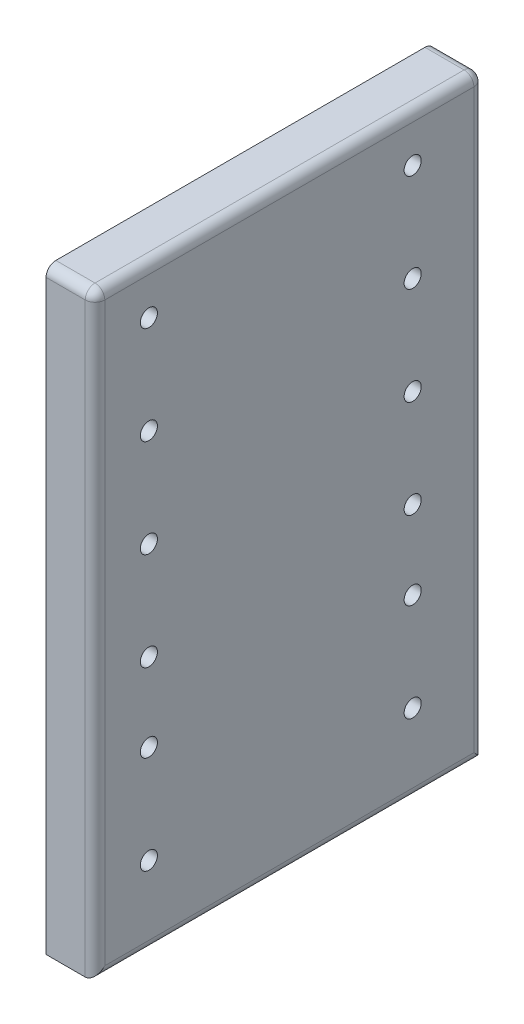
SolidWorks part; units mm, degrees
ref_plane "Front Plane" through (0, 0, 0) normal (0, 0, 1) x (1, 0, 0)
ref_plane "Top Plane" through (0, 0, 0) normal (0, 1, 0) x (1, 0, 0)
ref_plane "Right Plane" through (0, 0, 0) normal (1, 0, 0) x (0, 0, -1)
sketch "Sketch1" plane through (0, 0, 0) normal (1, 0, 0) x (0, 0, -1)
  line L0 (0, 0) -> (0, 106.1534) construction
  line L1 (0, 0) -> (0, -12.5474) construction
  point P3 (0, 0)
  point P4 (12.8932, -2.1128)
  point P5 (0, 0)
  point P7 (0, 106.1534)
  line B0 (-35, 97.3427) -> (-35, -0.6573)
  line B1 (-37, -0.6573) -> (-37, 98.3427)
  arc B2 (-36, 99.3427) -> (-37, 98.3427) centre (-36, 98.3427) ccw
  line B3 (35, -0.6573) -> (35, 97.3427)
  line B4 (37, 98.3427) -> (37, -0.6573)
  line B5 (35, 97.3427) -> (-35, 97.3427)
  line B6 (-36, 99.3427) -> (36, 99.3427)
  arc B7 (37, 98.3427) -> (36, 99.3427) centre (36, 98.3427) ccw
  line B8 (37, -0.6573) -> (35, -0.6573)
  line B9 (37.9, 1.6427) -> (38.4, 1.6427)
  line B10 (37.9, 1.6427) -> (37.4, 1.1427)
  line B11 (37.4, 1.1427) -> (37.4, -1.3573)
  line B12 (35, -1.3573) -> (37.4, -1.3573)
  line B13 (35, -1.3573) -> (35, -15.8573)
  line B14 (-33, -17.8573) -> (33, -17.8573)
  line B15 (-35, -1.3573) -> (-35, -15.8573)
  line B16 (-37.4, -1.3573) -> (-35, -1.3573)
  line B17 (-37.4, 1.1427) -> (-37.4, -1.3573)
  line B18 (-37.4, 1.1427) -> (-37.9, 1.6427)
  line B19 (-38.4, 1.6427) -> (-37.9, 1.6427)
  line B20 (-38.4, 1.6427) -> (-38.4, -19.8573)
  line B21 (-38.4, -19.8573) -> (38.4, -19.8573)
  line B22 (38.4, 1.6427) -> (38.4, -19.8573)
  arc B23 (33, -17.8573) -> (35, -15.8573) centre (33, -15.8573) ccw
  arc B24 (-35, -15.8573) -> (-33, -17.8573) centre (-33, -15.8573) ccw
  dimension "D1" = 0.7
sketch_block_instance "Body2BackPlat-1"
sketch_block "Body2BackPlat"
sketch_block_instance "bottomCup1BackPlat-1"
sketch_block "bottomCup1BackPlat"
sketch "Sketch2" plane through (0, 0, 0) normal (1, 0, 0) x (0, 0, -1)
  line L0 (0, 0) -> (0, 111.6964) construction
  line L1 (-39.7, 100.6427) -> (39.7, 100.6427)
  line L2 (-39.7, 100.6427) -> (-39.7, -21.1573)
  line L3 (-39.7, -21.1573) -> (39.7, -21.1573)
  line L4 (39.7, 100.6427) -> (39.7, -21.1573)
  point P4 (0, 0)
  dimension "D1" = 1.3
  dimension "D2" = 1.3
  dimension "D3" = 1.3
extrude "Boss-Extrude1" add sketch "Sketch2" along normal blind 10
sketch "Sketch3" plane through (0, 0, 0) normal (1, 0, 0) x (0, 0, -1)
  line L0 (34.7, -15.8573) -> (34.7, -16.9692) construction
  line L1 (34.7, -16.9692) -> (-34.7, -16.9692) construction
  line L2 (-34.7, -15.8573) -> (-34.7, -16.9692)
  line L4 (-34.7, -16.9692) -> (34.7, -16.9692)
  line L5 (34.7, -16.9692) -> (34.7, -15.8573)
  line L6 (-38.7, 1.9427) -> (-38.7, 2.9406)
  line L7 (-38.7, 2.9406) -> (-37.3, 2.9406)
  line L8 (38.7, 1.9427) -> (38.7, 2.9406)
  line L9 (38.7, 2.9406) -> (37.3, 2.9406)
  line L33 (37.3, 98.3427) -> (37.3, -0.6573)
  line L34 (-37.3, -0.6573) -> (-37.3, 98.3427)
  line L35 (-36, 99.6427) -> (36, 99.6427)
  line L36 (37.3, 98.3427) -> (37.3, 2.9406)
  line L38 (-36, 99.6427) -> (36, 99.6427)
  line L51 (-34.7, 97.0427) -> (-34.7, -0.6573)
  line L52 (34.7, 97.0427) -> (-34.7, 97.0427)
  line L53 (34.7, -0.6573) -> (34.7, 97.0427)
  line L54 (-34.7, 97.0427) -> (-34.7, -0.6573)
  line L55 (34.7, 97.0427) -> (-34.7, 97.0427)
  line L56 (34.7, -0.6573) -> (34.7, 97.0427)
  line L168 (34.7, -0.6573) -> (34.7, -1.0573)
  line L169 (-34.7, -0.6573) -> (-34.7, -1.0573)
  line L171 (-37.3, 2.9406) -> (-37.3, 98.3427)
  line L181 (37.1, -1.0573) -> (34.7, -1.0573)
  line L182 (37.1, 1.267) -> (37.1, -1.0573)
  line L183 (37.7757, 1.9427) -> (37.1, 1.267)
  line L184 (38.7, 1.9427) -> (37.7757, 1.9427)
  line L185 (38.7, -20.1573) -> (38.7, 1.9427)
  line L186 (-38.7, -20.1573) -> (38.7, -20.1573)
  line L187 (-38.7, 1.9427) -> (-38.7, -20.1573)
  line L188 (-37.7757, 1.9427) -> (-38.7, 1.9427)
  line L189 (-37.1, 1.267) -> (-37.7757, 1.9427)
  line L190 (-37.1, -1.0573) -> (-37.1, 1.267)
  line L191 (-34.7, -1.0573) -> (-37.1, -1.0573)
  line L192 (-34.7, -15.8573) -> (-34.7, -1.0573)
  line L193 (33, -17.5573) -> (-33, -17.5573)
  line L194 (34.7, -1.0573) -> (34.7, -15.8573)
  line L199 (38.7, -20.1573) -> (38.7, 1.9427)
  line L200 (-38.7, -20.1573) -> (38.7, -20.1573)
  line L201 (-38.7, 1.9427) -> (-38.7, -20.1573)
  line L206 (-34.7, -15.8573) -> (-34.7, -1.0573)
  line L208 (34.7, -1.0573) -> (34.7, -15.8573)
  arc A26 (-36, 99.6427) -> (-37.3, 98.3427) centre (-36, 98.3427) ccw
  arc A27 (37.3, 98.3427) -> (36, 99.6427) centre (36, 98.3427) ccw
  arc A28 (-36, 99.6427) -> (-37.3, 98.3427) centre (-36, 98.3427) ccw
  arc A29 (37.3, 98.3427) -> (36, 99.6427) centre (36, 98.3427) ccw
  arc A60 (-34.7, -15.8573) -> (-33, -17.5573) centre (-33, -15.8573) ccw
  arc A61 (33, -17.5573) -> (34.7, -15.8573) centre (33, -15.8573) ccw
  dimension "D4" = 1.1119
  dimension "D5" = 23.0979
  dimension "D1" = 0.3
  dimension "D2" = 0.3
  dimension "D3" = 0.3
extrude "Cut-Extrude1" cut sketch "Sketch3" along normal blind 3
sketch "Sketch7" plane through (0, 0, 0) normal (-1, 0, 0) x (0, 0, 1)
  line L0 (-34.7, 97.0427) -> (34.7, 97.0427) construction
  line L1 (-33.2, 95.5427) -> (33.2, 95.5427)
  line L2 (-33.2, 95.5427) -> (-33.2, -15.4692)
  line L3 (-33.2, -15.4692) -> (33.2, -15.4692)
  line L4 (33.2, 95.5427) -> (33.2, -15.4692)
  line L5 (34.7, 97.0427) -> (34.7, -16.9692) construction
  line L6 (34.7, -16.9692) -> (-34.7, -16.9692) construction
  line L7 (-34.7, -16.9692) -> (-34.7, 97.0427) construction
  point P4 (-33.3693, 95.3578)
  dimension "D1" = 1.5
  dimension "D2" = 1.5
  dimension "D3" = 1.5
  dimension "D4" = 1.5
extrude "Cut-Extrude4" cut sketch "Sketch7" against normal offset from surface (7.5 mm away) 2.5 up to face at (10, 39.7427, 0)
fillet "Fillet2" radius 2 16 edges at (10, 100.6427, 0) (10, 39.7427, -39.7) (10, -21.1573, 0) (10, 39.7427, 39.7) (7.5, 95.5427, 0) (7.5, 40.0368, 33.2) (7.5, -15.4692, 0) (7.5, 40.0368, -33.2) (3.75, 95.5427, 33.2) (3.75, 95.5427, -33.2) (3.75, -15.4692, 33.2) (3.75, -15.4692, -33.2) (5, 100.6427, 39.7) (5, 100.6427, -39.7) (1.5, -16.9692, 34.7) (1.5, -16.9692, -34.7)
sketch "Sketch6" plane through (10, 0, 0) normal (1, 0, 0) x (0, 0, -1)
  line L0 (0, 0) -> (0, 143.7575) construction
  line L1 (0, 0) -> (0, -50.4822) construction
  circle A0 centre (-28.7, 91) radius 1.75
  circle A6 centre (25.2, 91) radius 1.75
  circle A7 centre (-28.7, 71) radius 1.75
  circle A8 centre (-28.7, 51) radius 1.75
  circle A9 centre (-28.7, 31) radius 1.75
  circle A10 centre (25.2, 31) radius 1.75
  circle A11 centre (25.2, 51) radius 1.75
  circle A12 centre (25.2, 71) radius 1.75
  circle A13 centre (-28.7, 15) radius 1.75
  circle A14 centre (25.2, 15) radius 1.75
  circle A15 centre (-28.7, -5) radius 1.75
  circle A16 centre (25.2, -5) radius 1.75
  dimension "D1" = 91
  dimension "D3" = 3.5
  dimension "D4" = 76
  dimension "D5" = 4
  dimension "D2" = 28.7
  dimension "D6" = 53.9
  dimension "D7" = 20
  dimension "D8" = 2
  dimension "D9" = 20
extrude "Cut-Extrude5" cut sketch "Sketch6" against normal blind 26.5
